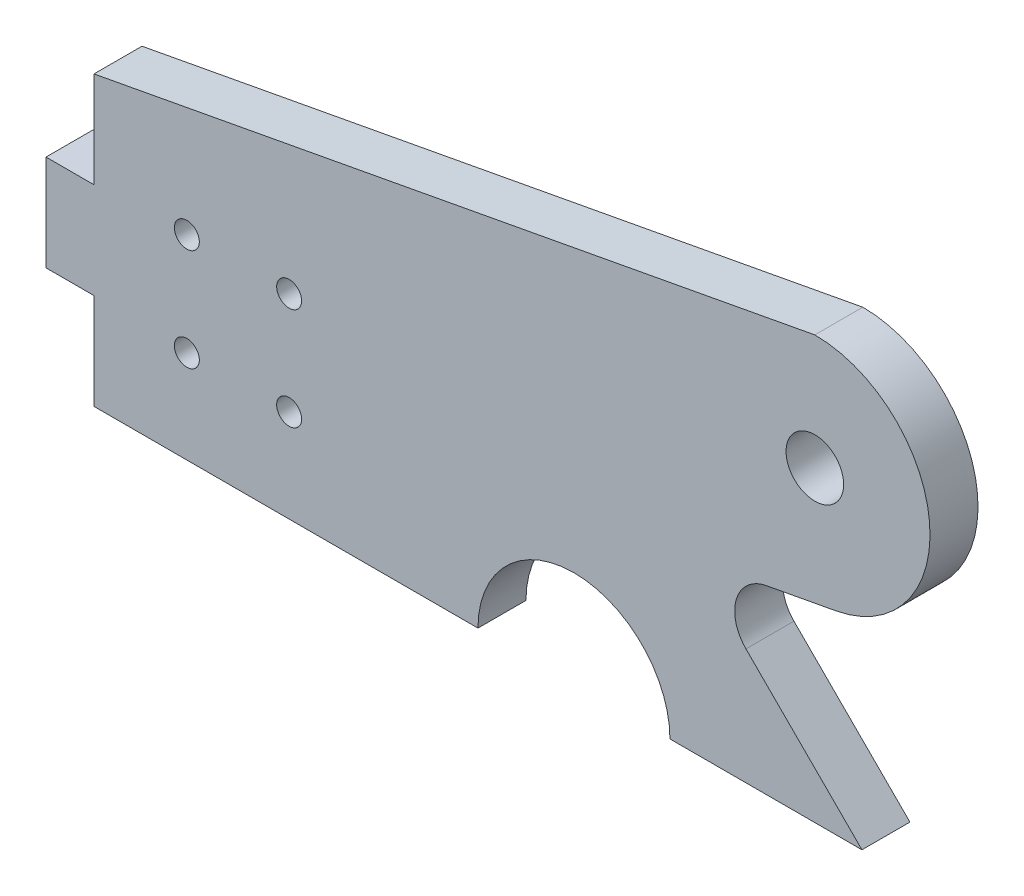
SolidWorks part; units mm, degrees
ref_plane "Front Plane" through (0, 0, 0) normal (0, 0, 1) x (1, 0, 0)
ref_plane "Top Plane" through (0, 0, 0) normal (0, 1, 0) x (1, 0, 0)
ref_plane "Right Plane" through (0, 0, 0) normal (1, 0, 0) x (0, 0, -1)
sketch "Sketch1" plane through (0, 0, 0) normal (0, 0, 1) x (1, 0, 0)
  line L0 (0, 0) -> (101.6, 0)
  line L3 (0, 38.1) -> (0, 25.4)
  line L4 (95.3675, 55.88) -> (0, 38.1)
  line L5 (0, 19.05) -> (100.2273, 19.05) construction
  line L6 (19.05, 19.05) -> (19.05, 28.62) construction
  line L7 (19.05, 19.05) -> (25.817, 25.817) construction
  line L8 (101.6, 0) -> (79.4333, 22.1667)
  line L9 (79.4333, 22.1667) -> (98.1606, 25.6582)
  line L10 (0, 12.7) -> (0, 0)
  line L11 (0, 25.4) -> (-6.35, 25.4)
  line L13 (0, 12.7) -> (-6.35, 12.7)
  line L14 (-6.35, 25.4) -> (-6.35, 12.7)
  arc A0 (98.1606, 25.6582) -> (95.3675, 55.88) centre (95.3675, 40.64) ccw
  circle A1 centre (95.3675, 40.64) radius 3.81
  circle A2 centre (19.05, 19.05) radius 9.57 construction
  circle A3 centre (25.817, 25.817) radius 1.651
  circle A4 centre (25.817, 12.283) radius 1.651
  circle A5 centre (12.283, 12.283) radius 1.651
  circle A6 centre (12.283, 25.817) radius 1.651
  point P26 (19.05, 19.05)
  dimension "D1" = 7.62
  dimension "D5" = 15.24
  dimension "D4" = 19.14
  dimension "D7" = 3.302
  dimension "D11" = 19.05
  dimension "D2" = 38.1
  dimension "D3" = 40.64
  dimension "D6" = 101.6
  dimension "D8" = 45
  dimension "D9" = 4
  dimension "D10" = 19.05
  dimension "D12" = 45
  dimension "D13" = 0
  dimension "D14" = 12.7
  dimension "D15" = 12.7
  dimension "D16" = 6.35
extrude "Boss-Extrude1" add sketch "Sketch1" along normal blind 6.35
sketch "Sketch2" plane through (0, 0, 6.35) normal (0, 0, 1) x (1, 0, 0)
  circle A0 centre (95.3675, 40.64) radius 38.1 construction
fillet "Fillet2" radius 5.08 1 edges at (79.4333, 22.1667, 3.175)
sketch "Sketch3" plane through (0, 0, 0) normal (-1, 0, 0) x (0, 0, 1)
  line L0 (0, 38.1) -> (6.35, 25.4) construction
  line L1 (6.35, 12.7) -> (0, 0) construction
  circle A0 centre (3.175, 31.75) radius 1.5875
  circle A1 centre (3.175, 6.35) radius 1.5875
  dimension "D1" = 3.175
  dimension "D2" = 3.175
extrude "Cut-Extrude1" cut sketch "Sketch3" against normal blind 6.35
sketch "Sketch6" plane through (0, 0, 6.35) normal (0, 0, 1) x (1, 0, 0)
  line L0 (0, 0) -> (101.6, 0) construction
  line L1 (50.8, 0) -> (76.2, 0)
  arc A0 (76.2, 0) -> (50.8, 0) centre (63.5, 0) ccw
  dimension "D1" = 25.4
  dimension "D2" = 25.4
extrude "Cut-Extrude2" cut sketch "Sketch6" against normal blind 6.35
